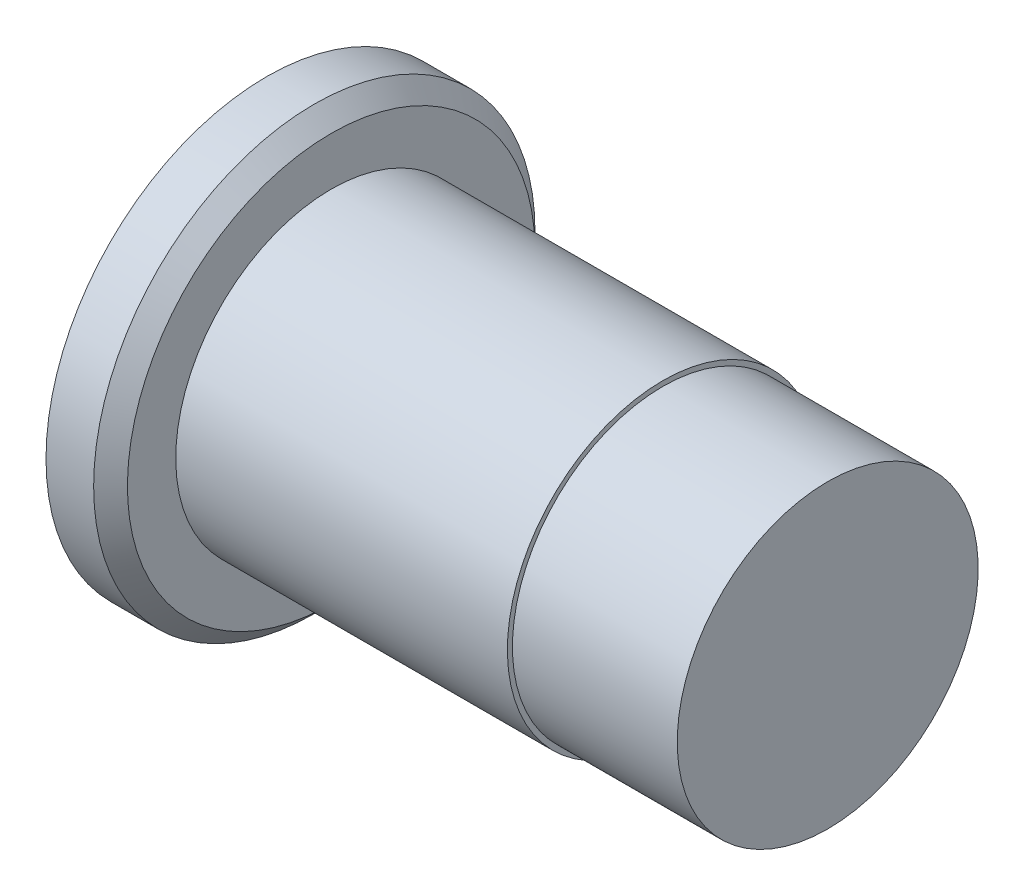
SolidWorks part; units mm, degrees
ref_plane "Front Plane" through (0, 0, 0) normal (0, 0, 1) x (1, 0, 0)
ref_plane "Top Plane" through (0, 0, 0) normal (0, 1, 0) x (1, 0, 0)
ref_plane "Right Plane" through (0, 0, 0) normal (1, 0, 0) x (0, 0, -1)
sketch "Sketch1" plane through (0, 0, 0) normal (0, 0, 1) x (1, 0, 0)
  line L0 (0, 0) -> (0, 31)
  line L1 (0, 31) -> (7, 31)
  line L2 (7, 31) -> (7, 44)
  line L3 (7, 44) -> (16.5, 44)
  line L4 (16.5, 44) -> (19.87, 40.63)
  line L5 (19.87, 40.63) -> (19.87, 31)
  line L6 (19.87, 31) -> (118.87, 31)
  line L7 (118.87, 31) -> (118.87, 0)
  line L8 (118.87, 0) -> (0, 0)
  point P3 (7, 37.5)
  dimension "D1" = 31
  dimension "D2" = 37.5
  dimension "D3" = 3.37
  dimension "D4" = 135
  dimension "D5" = 7
  dimension "D6" = 9.5
  dimension "D7" = 99
revolve "Revolve1" add sketch "Sketch1" angle 360 about L8
sketch "Sketch3" plane through (7, 0, 0) normal (-1, 0, 0) x (0, 0, 1)
  line L0 (0, 0) -> (0, 37.5) construction
  circle A0 centre (0, 37.5) radius 4
  dimension "D2" = 8
  dimension "D1" = 37.5
extrude "Cut-Extrude5" cut sketch "Sketch3" against normal blind 10
pattern_circular "CirPattern1" count 6 over 360 about axis through (0, 0, 0) along (1, 0, 0) of "Cut-Extrude5"
sketch "Sketch4" plane through (0, 0, 0) normal (-1, 0, 0) x (0, 0, 1)
  circle A0 centre (0, 0) radius 23.5
  dimension "D1" = 47
extrude "Cut-Extrude6" cut sketch "Sketch4" against normal blind 90
sketch "Sketch5" plane through (0, 0, 0) normal (0, 0, 1) x (1, 0, 0)
  line L0 (118.87, 0) -> (118.87, 26) construction
  line L1 (118.87, -31) -> (118.87, 31) construction
  line L2 (118.87, 26) -> (90, 26) construction
  line L3 (90, 23.5) -> (90, -23.5) construction
  line L5 (74, 10) -> (90, 10)
  line L6 (90, 10) -> (90, 26)
  line L7 (118.87, 0) -> (90, 0) construction
  line L8 (74, 10) -> (74, 26)
  line L9 (74, 26) -> (90, 26)
  dimension "D1" = 26
  dimension "D2" = 10
revolve "Revolve2" add sketch "Sketch5" angle 360 about L7
ref_plane "Plane1" through (74, 0, 0) normal (-1, 0, 0) x (0, 0, 1)
sketch "Sketch6" plane through (74, 0, 0) normal (-1, 0, 0) x (0, 0, 1)
  line L0 (0, 0) -> (0, 11) construction
  line L1 (-1, 11) -> (1, 11)
  line L2 (1, 11) -> (1, 8.6)
  line L3 (1, 8.6) -> (-1, 8.6)
  line L4 (-1, 11) -> (-1, 8.6)
  point P8 (0, 8.6)
  dimension "D1" = 11
  dimension "D2" = 1
  dimension "D3" = 2.4
extrude "Boss-Extrude1" add sketch "Sketch6" along normal up to surface (16 mm away)
pattern_circular "CirPattern2" count 12 over 360 about axis through (0, 0, 0) along (1, 0, 0) of "Boss-Extrude1"
sketch "Sketch7" plane through (118.87, 0, 0) normal (1, 0, 0) x (0, 0, -1)
  circle A0 centre (0, 0) radius 30
  circle A1 centre (0, 0) radius 31
  dimension "D1" = 60
  dimension "D2" = 62
extrude "Cut-Extrude7" cut sketch "Sketch7" against normal blind 32.87
